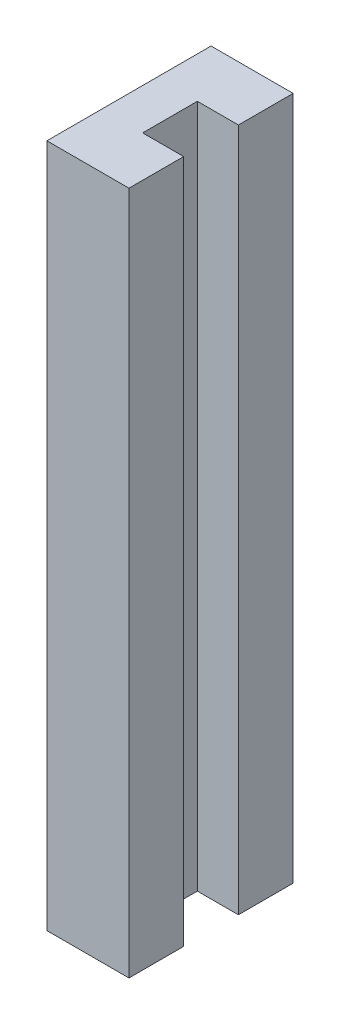
SolidWorks part; units mm, degrees
ref_plane "Front" through (0, 0, 0) normal (0, 0, 1) x (1, 0, 0)
ref_plane "Top" through (0, 0, 0) normal (0, 1, 0) x (1, 0, 0)
ref_plane "Right" through (0, 0, 0) normal (1, 0, 0) x (0, 0, -1)
other "Configuration Table"
sketch "Sketch1" plane through (0, 0, 0) normal (0, 1, 0) x (1, 0, 0)
  line L0 (0, 0) -> (0, -12)
  line L1 (0, -12) -> (6, -12)
  line L2 (6, -12) -> (6, -8)
  line L3 (6, -8) -> (3, -8)
  line L4 (0, 0) -> (6, 0)
  line L5 (6, 0) -> (6, -4)
  line L6 (6, -4) -> (3, -4)
  line L7 (3, -4) -> (3, -8)
  dimension "D1" = 12
  dimension "D2" = 6
  dimension "D3" = 4
  dimension "D4" = 4
  dimension "D5" = 3
extrude "Boss-Extrude1" add sketch "Sketch1" along normal blind 50
